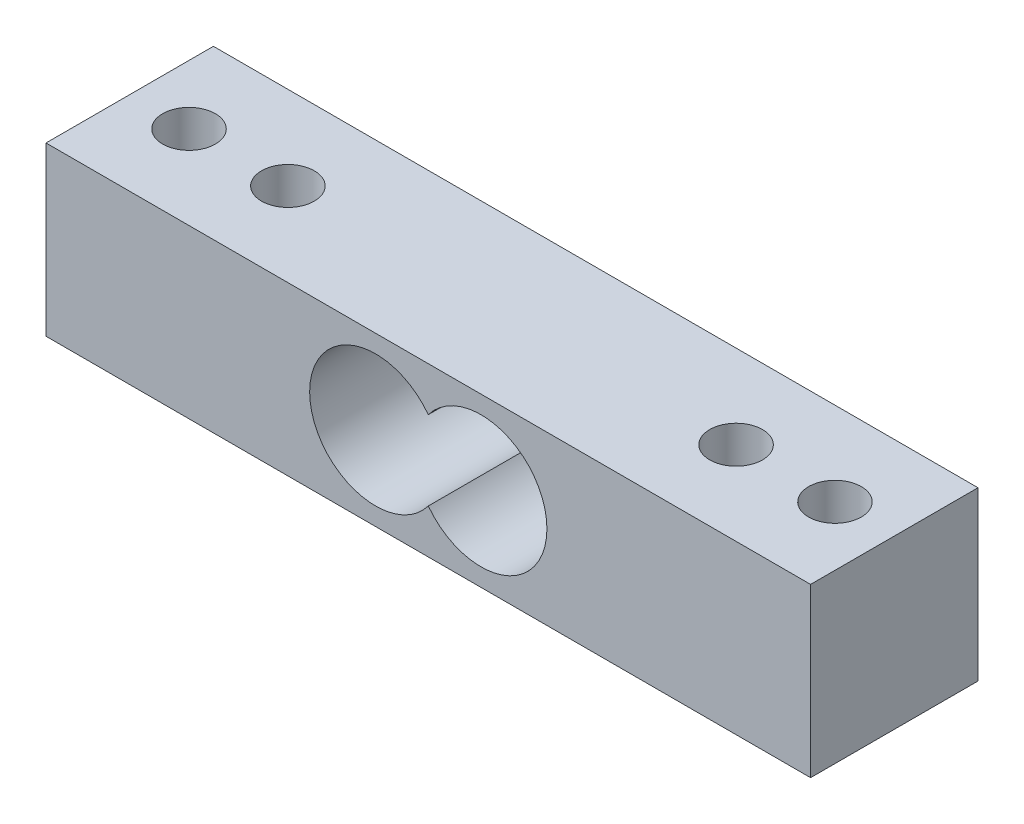
SolidWorks part; units mm, degrees
ref_plane "Ebene vorne" through (0, 0, 0) normal (0, 0, 1) x (1, 0, 0)
ref_plane "Ebene oben" through (0, 0, 0) normal (0, 1, 0) x (1, 0, 0)
ref_plane "Ebene rechts" through (0, 0, 0) normal (1, 0, 0) x (0, 0, -1)
sketch "Skizze1" plane through (0, 0, 0) normal (0, 1, 0) x (1, 0, 0)
  line L0 (-29, 0) -> (-24.5, 0) construction
  line L1 (-29, 6.35) -> (29, 6.35)
  line L2 (-29, 6.35) -> (-29, -6.35)
  line L3 (-29, -6.35) -> (29, -6.35)
  line L4 (29, 6.35) -> (29, -6.35)
  line L5 (-29, 6.35) -> (29, -6.35) construction
  line L6 (-29, -6.35) -> (29, 6.35) construction
  line L7 (-24.5, 0) -> (-17, 0) construction
  line L8 (29, 0) -> (24.5, 0) construction
  line L9 (24.5, 0) -> (17, 0) construction
  circle A0 centre (-24.5, 0) radius 2
  circle A1 centre (-17, 0) radius 2
  circle A2 centre (24.5, 0) radius 2
  circle A3 centre (17, 0) radius 2
  point P0 (0, 0)
extrude "Aufsatz-Linear austragen1" add sketch "Skizze1" along normal blind 12.7
sketch "Skizze2" plane through (0, 0, 6.35) normal (0, 0, 1) x (1, 0, 0)
  line L0 (0, 0) -> (0, 12.7) construction
  line L1 (-29, 0) -> (29, 0) construction
  line L2 (-29, 12.7) -> (29, 12.7) construction
  line L3 (0, 6.35) -> (4, 6.35) construction
  line L4 (0, 6.35) -> (-4, 6.35) construction
  circle A0 centre (-4, 6.35) radius 5
  circle A1 centre (4, 6.35) radius 5
extrude "Schnitt-Linear austragen1" cut sketch "Skizze2" against normal blind 12.7 contours A0 A1 | A1 A0 | A0 A1
